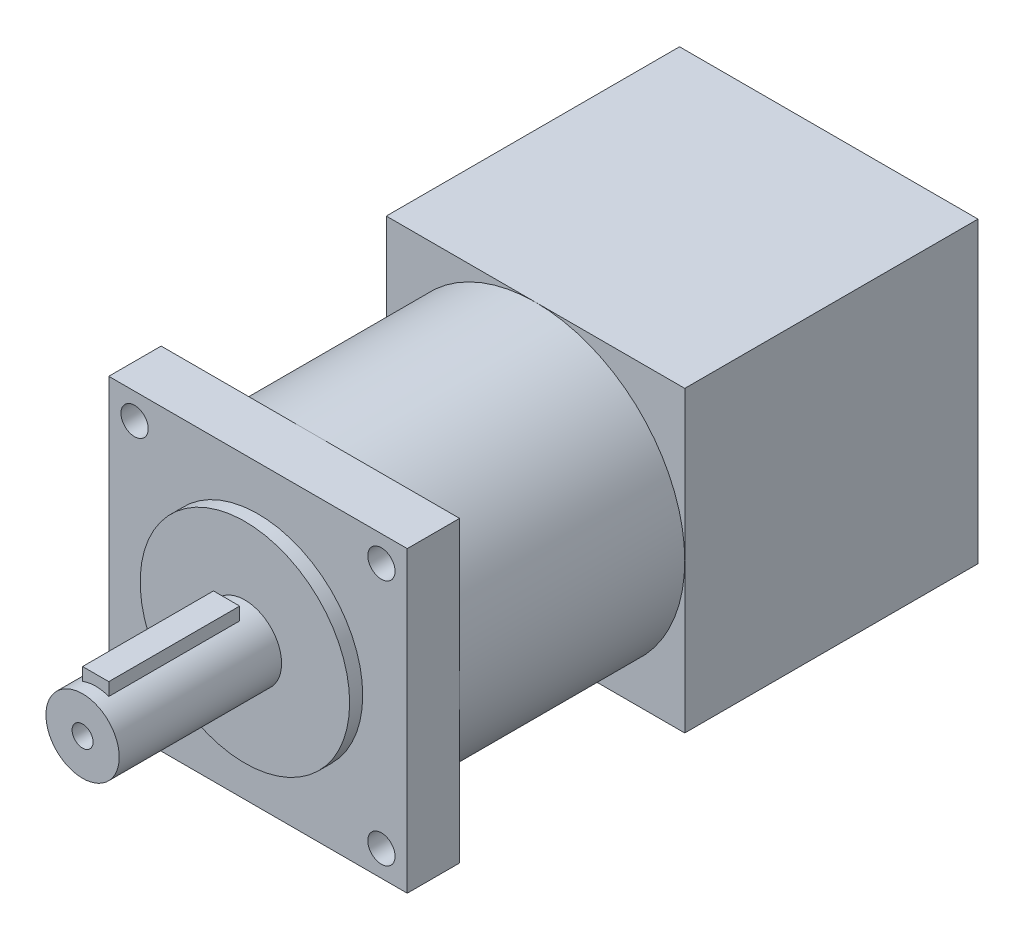
SolidWorks part; units mm, degrees
ref_plane "前视基准面" through (0, 0, 0) normal (0, 0, 1) x (1, 0, 0)
ref_plane "上视基准面" through (0, 0, 0) normal (0, 1, 0) x (1, 0, 0)
ref_plane "右视基准面" through (0, 0, 0) normal (1, 0, 0) x (0, 0, -1)
sketch "草图1" plane through (0, 0, 0) normal (0, 0, 1) x (1, 0, 0)
  line L1 (-28.5, 28.5) -> (28.5, 28.5)
  line L2 (-28.5, 28.5) -> (-28.5, -28.5)
  line L3 (-28.5, -28.5) -> (28.5, -28.5)
  line L4 (28.5, 28.5) -> (28.5, -28.5)
  line L5 (-28.5, 28.5) -> (28.5, -28.5) construction
  line L6 (-28.5, -28.5) -> (28.5, 28.5) construction
  point P0 (0, 0)
  dimension "D1" = 57
extrude "凸台-拉伸1" add sketch "草图1" along normal blind 56
sketch "草图2" plane through (0, 0, 56) normal (0, 0, 1) x (1, 0, 0)
  circle A0 centre (0, 0) radius 28.5
  dimension "D1" = 57
extrude "凸台-拉伸2" add sketch "草图2" along normal blind 53
sketch "草图3" plane through (0, 0, 109) normal (0, 0, 1) x (1, 0, 0)
  circle A0 centre (0, 0) radius 20
  dimension "D1" = 40
extrude "凸台-拉伸3" add sketch "草图3" along normal blind 2.5
sketch "草图4" plane through (0, 0, 111.5) normal (0, 0, 1) x (1, 0, 0)
  circle A0 centre (0, 0) radius 7
  dimension "D1" = 14
extrude "凸台-拉伸4" add sketch "草图4" along normal blind 31
sketch "草图7" plane through (0, 0, 109) normal (0, 0, 1) x (1, 0, 0)
  line L0 (-23.57, 23.57) -> (23.57, 23.57) construction
  line L1 (-28.5, -28.5) -> (28.5, -28.5)
  line L2 (-28.5, -28.5) -> (-28.5, 28.5)
  line L3 (-28.5, 28.5) -> (28.5, 28.5)
  line L4 (28.5, -28.5) -> (28.5, 28.5)
  line L5 (-28.5, -28.5) -> (28.5, 28.5) construction
  line L6 (-28.5, 28.5) -> (28.5, -28.5) construction
  circle A0 centre (-23.57, 23.57) radius 2.6
  circle A1 centre (23.57, 23.57) radius 2.6
  circle A2 centre (23.57, -23.57) radius 2.6
  circle A3 centre (-23.57, -23.57) radius 2.6
  point P0 (0, 0)
  dimension "D3" = 5.2
  dimension "D1" = 57
  dimension "D2" = 47.14
extrude "凸台-拉伸5" add sketch "草图7" against normal blind 10
ref_plane "基准面1" through (0, 0, 140) normal (0, 0, 1) x (1, 0, 0)
sketch "草图8" plane through (0, 0, 140) normal (0, 0, 1) x (1, 0, 0)
  line L1 (2.5, 5) -> (-2.5, 5)
  line L2 (2.5, 5) -> (2.5, 9)
  line L3 (2.5, 9) -> (-2.5, 9)
  line L4 (-2.5, 5) -> (-2.5, 9)
  line L5 (2.5, 5) -> (-2.5, 9) construction
  line L6 (2.5, 9) -> (-2.5, 5) construction
  circle A0 centre (0, 0) radius 7 construction
  circle A1 centre (0, 0) radius 7 construction
  point P0 (0, 7)
  dimension "D1" = 5
  dimension "D2" = 4
extrude "凸台-拉伸6" add sketch "草图8" against normal blind 25
sketch "草图9" plane through (0, 0, 142.5) normal (0, 0, 1) x (1, 0, 0)
  circle A0 centre (0, 0) radius 2
  dimension "D1" = 4
extrude "切除-拉伸1" cut sketch "草图9" against normal blind 6
